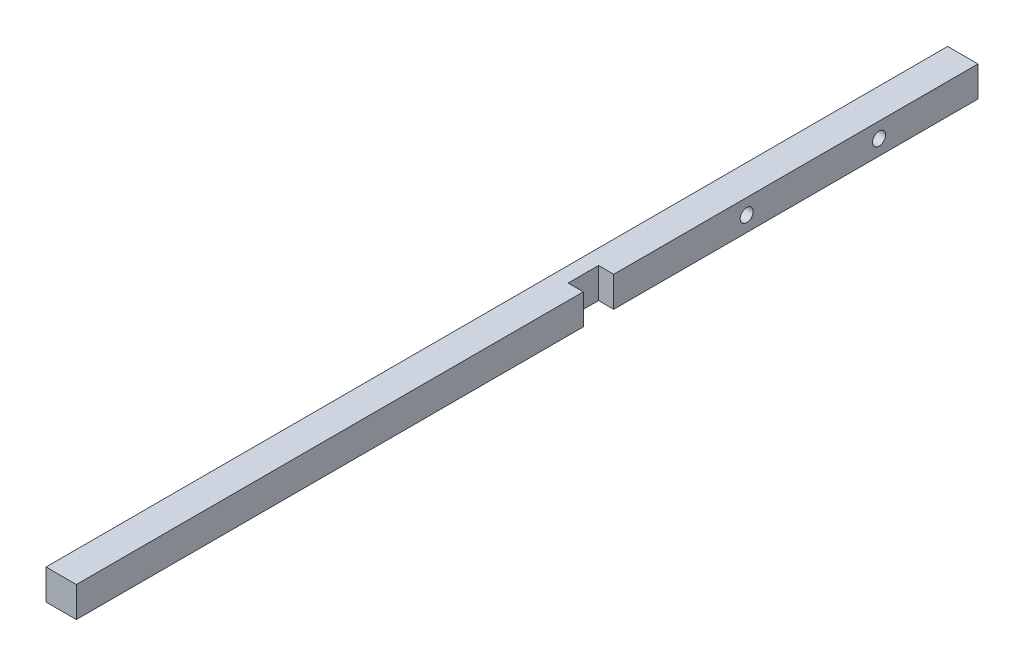
SolidWorks part; units mm, degrees
ref_plane "Plan de face" through (0, 0, 0) normal (0, 0, 1) x (1, 0, 0)
ref_plane "Plan de dessus" through (0, 0, 0) normal (0, 1, 0) x (1, 0, 0)
ref_plane "Plan de droite" through (0, 0, 0) normal (1, 0, 0) x (0, 0, -1)
sketch "Esquisse1" plane through (0, 0, 0) normal (0, 0, 1) x (1, 0, 0)
  line L0 (-5, 5) -> (5, -5) construction
  line L1 (-5, 5) -> (5, 5)
  line L2 (-5, 5) -> (-5, -5)
  line L3 (-5, -5) -> (5, -5)
  line L4 (5, 5) -> (5, -5)
  dimension "D1" = 10
extrude "Boss.-Extru.1" add sketch "Esquisse1" along normal offset from surface (307 mm away) 2
sketch "Esquisse2" plane through (0, 0, 0) normal (0, 1, 0) x (1, 0, 0)
  line L0 (-5, 0) -> (-5, -10)
  line L1 (-5, -10) -> (5, -10) construction
  line L2 (-5, -10) -> (5, -10)
  line L3 (5, -10) -> (5, 0)
  line L4 (5, 0) -> (-5, 0)
  line L5 (-5, -307) -> (-5, 0) construction
  line L6 (5, -307) -> (5, 0) construction
extrude "Enlèv. mat.-Extru.1" cut sketch "Esquisse2" against normal through all and the other way through all
sketch "Esquisse3" plane through (0, -5, 0) normal (0, -1, 0) x (1, 0, 0)
  line L0 (-5, 140) -> (0, 140) construction
  line L1 (0, 130) -> (5, 130)
  line L2 (0, 130) -> (0, 140)
  line L3 (0, 140) -> (5, 140)
  line L4 (5, 130) -> (5, 140)
  line L5 (5, 307) -> (5, 10) construction
extrude "Enlèv. mat.-Extru.2" cut sketch "Esquisse3" against normal through all
hole_wizard "Dégagement M41" positions "Esquisse5" profile "Esquisse4" hole size "M4" standard "Ansi Metric" end condition through all
sketch "Esquisse5" plane through (-5, 0, 0) normal (-1, 0, 0) x (0, 0, 1)
  point P0 (86.1865, 0)
  point P3 (42.5865, 0)
sketch "Esquisse4" plane through (-5, 0, 86.1865) normal (0, 1, 0) x (0, 0, 1)
  line L0 (0, 0) -> (0, 10)
  line L1 (0, 10) -> (2.15, 10)
  line L2 (2.15, 10) -> (2.15, 0)
  line L5 (2.15, 0) -> (0, 0)
  line L11 (0, -6.35) -> (0, 107.95) construction
  dimension "Diamètre du perçage jusqu'au prochain" = 4.3
  dimension "Profondeur du perçage jusqu'au prochain" = 10
hole_wizard "Trou taraudé M3x0.51" positions "Esquisse6" profile "Esquisse7" tap size "M3x0.5" standard "Ansi Metric"
sketch "Esquisse6" plane through (0, 0, 10) normal (0, 0, -1) x (-1, 0, 0)
  point P0 (0, 0)
sketch "Esquisse7" plane through (0, 0, 10) normal (1, 0, 0) x (0, 1, 0)
  line L0 (0, 0) -> (0, 8.5)
  line L1 (0, 8.5) -> (1.25, 8.5)
  line L2 (1.25, 8.5) -> (1.25, 0)
  line L5 (1.25, 0) -> (0, 0)
  line L10 (0, 8.5) -> (-1.25, 8.5) construction
  line L11 (0, -6.35) -> (0, 107.95) construction
  dimension "Diamètre du trou pour taraudage" = 2.5
  dimension "Profondeur du trou pour taraudage" = 8.5
  dimension "Angle de pointe" = 180
cosmetic thread "Filetage de perçage1" parameters "D1"=6, "D2"=3
